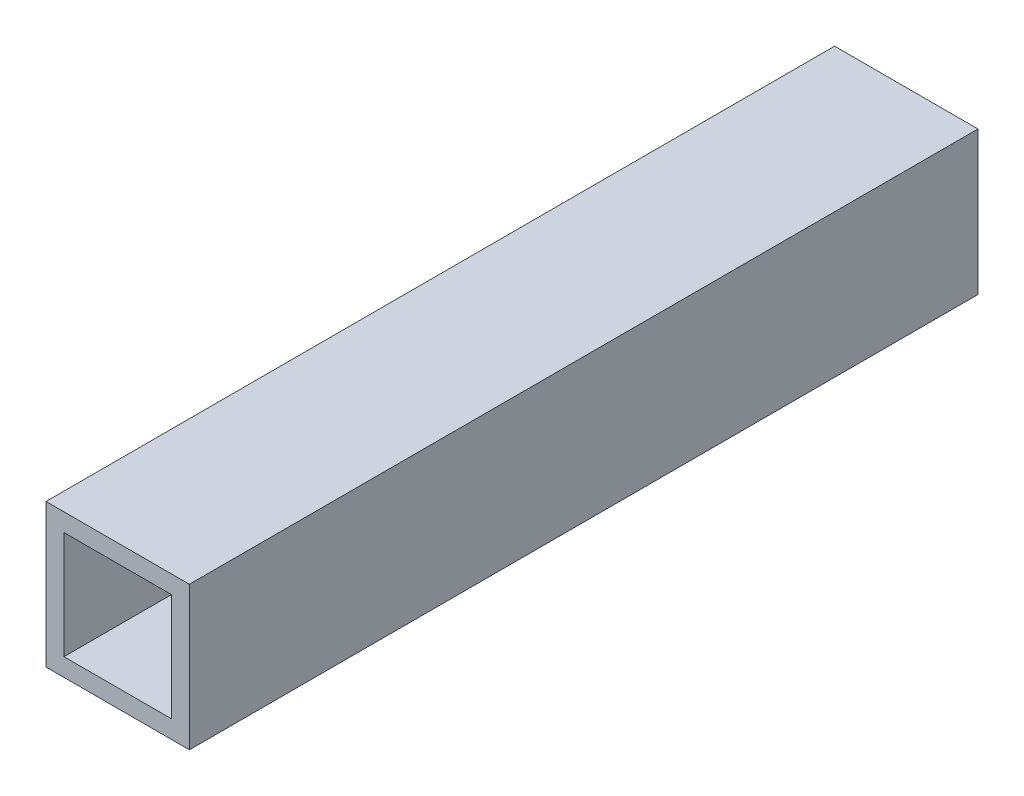
SolidWorks part; units mm, degrees
material "6061 Alloy"
ref_plane "Front" through (0, 0, 0) normal (0, 0, 1) x (1, 0, 0)
ref_plane "Top" through (0, 0, 0) normal (0, 1, 0) x (1, 0, 0)
ref_plane "Right" through (0, 0, 0) normal (1, 0, 0) x (0, 0, -1)
sketch "Sketch1" plane through (0, 0, 0) normal (0, 0, 1) x (1, 0, 0)
  line L1 (0, 0) -> (-25.4, 0)
  line L2 (0, 0) -> (0, 25.4)
  line L3 (0, 25.4) -> (-25.4, 25.4)
  line L4 (-25.4, 0) -> (-25.4, 25.4)
  line L5 (-3.175, 3.175) -> (-22.225, 3.175)
  line L6 (-3.175, 3.175) -> (-3.175, 22.225)
  line L7 (-3.175, 22.225) -> (-22.225, 22.225)
  line L8 (-22.225, 3.175) -> (-22.225, 22.225)
  dimension "D1" = 25.4
  dimension "D2" = 25.4
  dimension "D3" = 3.175
  dimension "D4" = 3.175
  dimension "D5" = 3.175
  dimension "D6" = 3.175
extrude "Boss-Extrude1" add sketch "Sketch1" along normal blind 139.7
